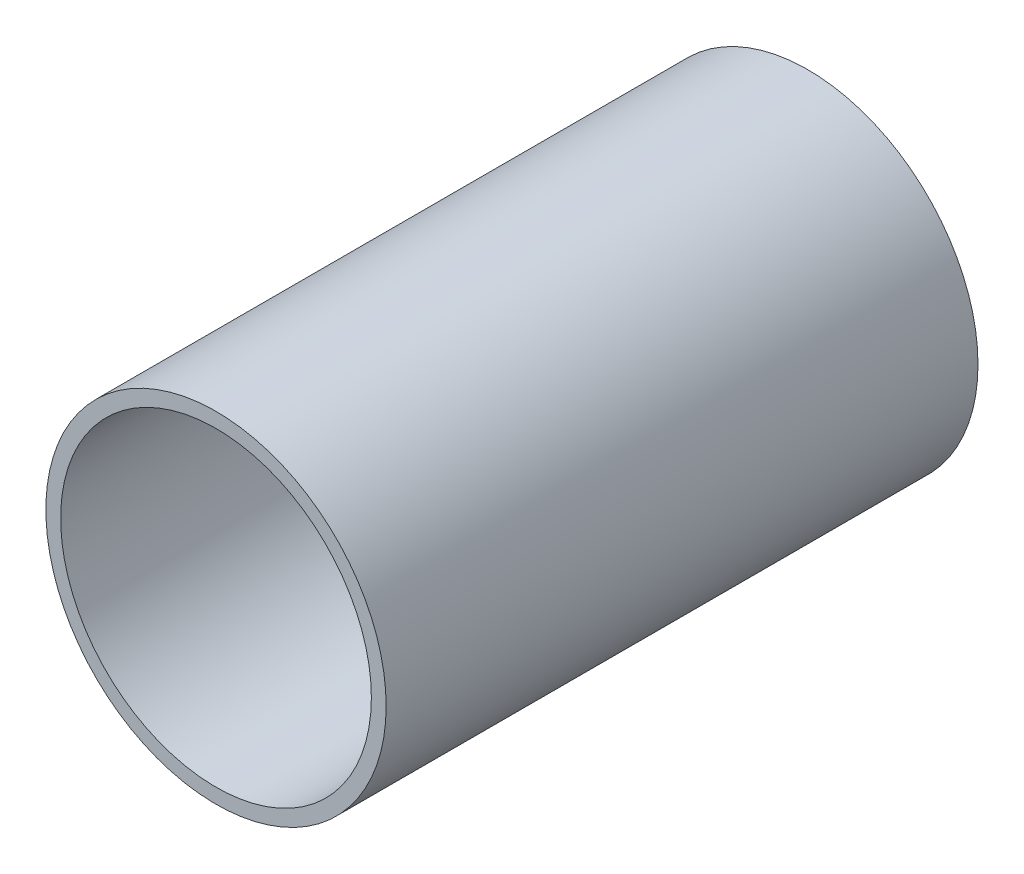
SolidWorks part; units mm, degrees
material "PVC Rigid"
ref_plane "Front Plane" through (0, 0, 0) normal (0, 0, 1) x (1, 0, 0)
ref_plane "Top Plane" through (0, 0, 0) normal (0, 1, 0) x (1, 0, 0)
ref_plane "Right Plane" through (0, 0, 0) normal (1, 0, 0) x (0, 0, -1)
sketch "Sketch1" plane through (0, 0, 0) normal (0, 0, 1) x (1, 0, 0)
  circle A0 centre (0, 0) radius 29.21
  circle A1 centre (0, 0) radius 26.67
  dimension "D1" = 58.42
  dimension "D2" = 2.54
extrude "Boss-Extrude1" add sketch "Sketch1" along normal mid plane 101.6
